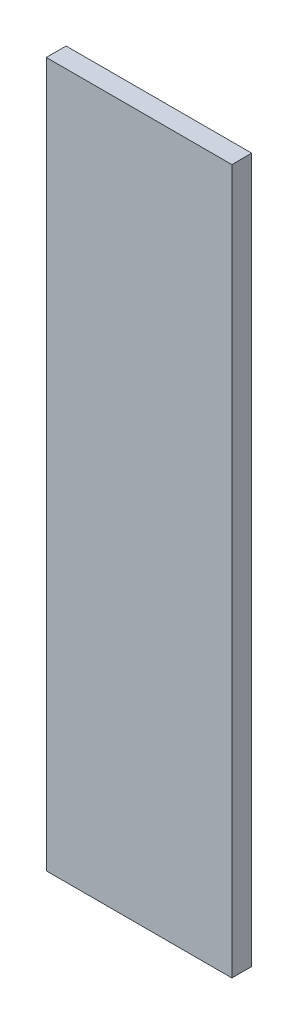
SolidWorks part; units mm, degrees
ref_plane "Front Plane" through (0, 0, 0) normal (0, 0, 1) x (1, 0, 0)
ref_plane "Top Plane" through (0, 0, 0) normal (0, 1, 0) x (1, 0, 0)
ref_plane "Right Plane" through (0, 0, 0) normal (1, 0, 0) x (0, 0, -1)
sketch "Sketch1" plane through (0, 0, 0) normal (0, 0, 1) x (1, 0, 0)
  line L0 (212, -36.5) -> (-18, -36.5) construction
  line L1 (12.7, -36.5) -> (181.3, -36.5)
  line L2 (12.7, -36.5) -> (12.7, 603.5)
  line L3 (12.7, 603.5) -> (181.3, 603.5)
  line L4 (181.3, -36.5) -> (181.3, 603.5)
  line L6 (181.3, -36.5) -> (181.3, 505.1122) construction
  line L7 (12.7, -35) -> (12.7, 506.6122) construction
  dimension "D1" = 640
extrude "Boss-Extrude1" add sketch "Sketch1" along normal blind 18
